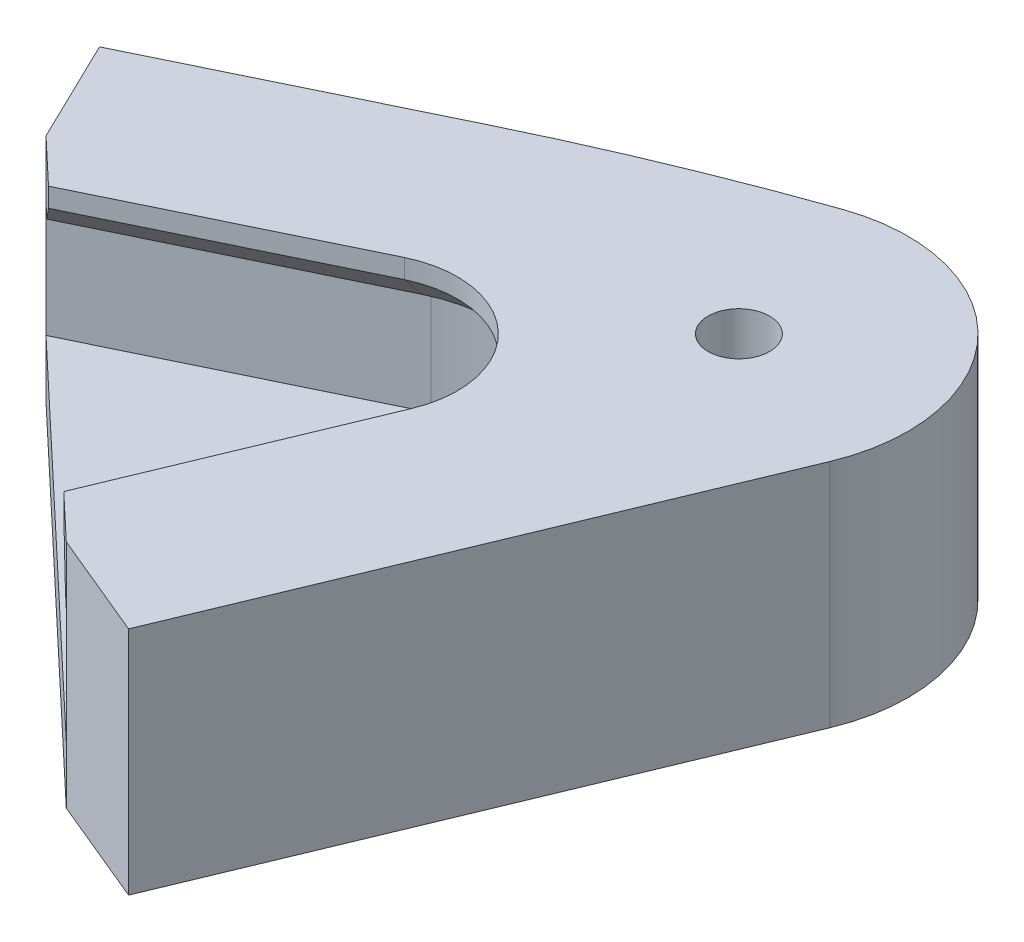
SolidWorks part; units mm, degrees
material "1060 Alloy"
ref_plane "Front Plane" through (0, 0, 0) normal (0, 0, 1) x (1, 0, 0)
ref_plane "Top Plane" through (0, 0, 0) normal (0, 1, 0) x (1, 0, 0)
ref_plane "Right Plane" through (0, 0, 0) normal (1, 0, 0) x (0, 0, -1)
sketch "Sketch1" plane through (0, 0, 0) normal (0, 1, 0) x (1, 0, 0)
  line L0 (-54.4954, 86.3958) -> (0, 60) construction
  line L1 (0, 60) -> (54.4954, 86.3958) construction
  line L2 (65.3716, 76.1292) -> (40, 15) construction
  line L3 (40, 15) -> (65.6883, -77.0455) construction
  line L4 (52.194, -84.7177) -> (0, -30) construction
  line L5 (0, -30) -> (-52.194, -84.7177) construction
  line L6 (-65.6883, -77.0455) -> (-40, 15) construction
  line L7 (-40, 15) -> (-65.3716, 76.1292) construction
  line L8 (-68.5894, 68.5894) -> (68.5894, -68.5894) construction
  line L9 (-42, 75) -> (-36, 75) construction
  line L10 (-42, 75) -> (-42, 55) construction
  line L11 (-42, 55) -> (-36, 55) construction
  line L12 (-36, 75) -> (-36, 55) construction
  line L13 (-42, 75) -> (-36, 55) construction
  line L14 (-42, 55) -> (-36, 75) construction
  line L15 (36, 75) -> (42, 75) construction
  line L16 (36, 75) -> (36, 55) construction
  line L17 (36, 55) -> (42, 55) construction
  line L18 (42, 75) -> (42, 55) construction
  line L19 (36, 75) -> (42, 55) construction
  line L20 (36, 55) -> (42, 75) construction
  line L21 (36, -45) -> (42, -45) construction
  line L22 (36, -45) -> (36, -65) construction
  line L23 (36, -65) -> (42, -65) construction
  line L24 (42, -45) -> (42, -65) construction
  line L25 (36, -45) -> (42, -65) construction
  line L26 (36, -65) -> (42, -45) construction
  line L27 (-42, -45) -> (-36, -45) construction
  line L28 (-42, -45) -> (-42, -65) construction
  line L29 (-42, -65) -> (-36, -65) construction
  line L30 (-36, -45) -> (-36, -65) construction
  line L31 (-42, -45) -> (-36, -65) construction
  line L32 (-42, -65) -> (-36, -45) construction
  line L33 (97, 40.1787) -> (40.1787, 97) construction
  line L34 (40.1787, 97) -> (-40.1787, 97) construction
  line L35 (-40.1787, 97) -> (-97, 40.1787) construction
  line L36 (-97, 40.1787) -> (-97, -40.1787) construction
  line L37 (-97, -40.1787) -> (-40.1787, -97) construction
  line L38 (-40.1787, -97) -> (40.1787, -97) construction
  line L39 (40.1787, -97) -> (97, -40.1787) construction
  line L40 (97, -40.1787) -> (97, 40.1787) construction
  line L41 (68.5894, 68.5894) -> (-68.5894, -68.5894) construction
  line L42 (40.9302, 79.992) -> (54.43, 86.5308)
  line L43 (111, -45.9777) -> (111, 45.9777) construction
  line L44 (111, 45.9777) -> (45.9777, 111) construction
  line L45 (45.9777, 111) -> (-45.9777, 111) construction
  line L46 (-45.9777, 111) -> (-111, 45.9777) construction
  line L47 (-111, 45.9777) -> (-111, -45.9777) construction
  line L48 (-111, -45.9777) -> (-45.9777, -111) construction
  line L49 (-45.9777, -111) -> (45.9777, -111) construction
  line L50 (45.9777, -111) -> (111, -45.9777) construction
  line L51 (65.5101, 76.0717) -> (59.76, 62.2176)
  line L52 (59.76, 62.2176) -> (65.3017, 59.9176)
  line L53 (65.3017, 59.9176) -> (76.0115, 85.7214)
  line L54 (40.9302, 79.992) -> (38.3147, 85.3919)
  line L55 (38.3147, 85.3919) -> (51.8144, 91.9307)
  circle A0 centre (-57.9828, 79.196) radius 1.5 construction
  circle A1 centre (57.9828, 79.196) radius 1.5 construction
  circle A2 centre (-57.9828, -79.196) radius 1.5 construction
  circle A3 centre (57.9828, -79.196) radius 1.5 construction
  arc A4 (-54.4954, 86.3958) -> (-65.3716, 76.1292) centre (-57.9828, 79.196) ccw construction
  arc A5 (54.4954, 86.3958) -> (65.3716, 76.1292) centre (57.9828, 79.196) cw construction
  arc A6 (-65.6883, -77.0455) -> (-52.194, -84.7177) centre (-57.9828, -79.196) ccw construction
  arc A7 (65.6883, -77.0455) -> (52.194, -84.7177) centre (57.9828, -79.196) cw construction
  circle A8 centre (0, 0) radius 97 construction
  circle A9 centre (-39, 65) radius 1.5 construction
  circle A10 centre (39, 65) radius 1.5 construction
  circle A11 centre (39, -55) radius 1.5 construction
  circle A12 centre (-39, -55) radius 1.5 construction
  circle A13 centre (0, 0) radius 111 construction
  arc A14 (54.43, 86.5308) -> (65.5101, 76.0717) centre (57.9828, 79.196) cw
  circle A15 centre (67.8823, 89.0955) radius 1.6
  arc A16 (76.0115, 85.7214) -> (64.9711, 97.4017) centre (67.8823, 89.0955) ccw
  arc A17 (51.8144, 91.9307) -> (64.9711, 97.4017) centre (106.3474, -20.6551) cw
  ellipse E0 centre (0, 15) end of major axis (0, 60) minor radius 40 construction
  dimension "D5" = 3
  dimension "D6" = 45
  dimension "D7" = 8
  dimension "D12" = 3
  dimension "D20" = 3.2
  dimension "D2" = 111
  dimension "D3" = 15
  dimension "D4" = 15
  dimension "D8" = 120
  dimension "D9" = 78
  dimension "D10" = 15
  dimension "D11" = 55
  dimension "D13" = 40
  dimension "D14" = 39
  dimension "D15" = 20
  dimension "D16" = 6
  dimension "D17" = 97
  dimension "D18" = 15
  dimension "D19" = 15
  dimension "D21" = 0.3
  dimension "D22" = 6
  dimension "D23" = 15
extrude "Boss-Extrude1" add sketch "Sketch1" along normal blind 6
sketch "Sketch7" plane through (0, 0, 0) normal (0, -1, 0) x (1, 0, 0)
  line L0 (76.0115, -85.7214) -> (65.3017, -59.9176)
  line L1 (65.3017, -59.9176) -> (59.76, -62.2176)
  line L2 (59.76, -62.2176) -> (40.9302, -79.992)
  line L3 (38.3147, -85.3919) -> (51.8144, -91.9307)
  line L4 (40.9302, -79.992) -> (38.3147, -85.3919)
  arc A0 (51.8144, -91.9307) -> (64.9711, -97.4017) centre (106.3474, 20.6551) ccw
  arc A1 (64.9711, -97.4017) -> (76.0115, -85.7214) centre (67.8823, -89.0955) ccw
  circle A2 centre (67.8823, -89.0955) radius 1.6
  circle A3 centre (57.9828, -79.196) radius 1.6
  circle A4 centre (67.8823, -89.0955) radius 1.6 construction
extrude "Boss-Extrude3" add sketch "Sketch7" along normal blind 3
sketch "Sketch8" plane through (0, 6, 0) normal (0, 1, 0) x (1, 0, 0)
  line L0 (38.3147, 85.3919) -> (40.9302, 79.992)
  line L1 (40.9302, 79.992) -> (43.264, 77.789)
  line L2 (59.76, 62.2176) -> (40.9302, 79.992) construction
  line L3 (43.264, 77.789) -> (55.7377, 83.8309)
  line L4 (62.7393, 77.2217) -> (57.4262, 64.4206)
  line L6 (57.4262, 64.4206) -> (59.76, 62.2176)
  line L7 (59.76, 62.2176) -> (65.3017, 59.9176)
  line L8 (65.3017, 59.9176) -> (76.0115, 85.7214)
  line L11 (51.8144, 91.9307) -> (38.3147, 85.3919)
  line L12 (40.9302, 79.992) -> (54.43, 86.5308) construction
  line L13 (65.5101, 76.0717) -> (59.76, 62.2176) construction
  arc A0 (55.7377, 83.8309) -> (62.7393, 77.2217) centre (57.9828, 79.196) cw
  arc A1 (76.0115, 85.7214) -> (64.9711, 97.4017) centre (67.8823, 89.0955) ccw
  arc A2 (64.9711, 97.4017) -> (51.8144, 91.9307) centre (106.3474, -20.6551) ccw construction
  arc A4 (64.9711, 97.4017) -> (51.8144, 91.9307) centre (106.3474, -20.6551) ccw
  circle A5 centre (67.8823, 89.0955) radius 1.6
  circle A6 centre (67.8823, 89.0955) radius 1.6 construction
  dimension "D1" = 3
extrude "Boss-Extrude4" add sketch "Sketch8" along normal blind 3
chamfer "Chamfer1" distance 2 angle 45 3 edges at (60.0828, 6, -70.8212) (61.5179, 6, -82.941) (49.5009, 6, -80.8099)
equation "\"D14@Sketch1\"=\"D9@Sketch1\"/2"
